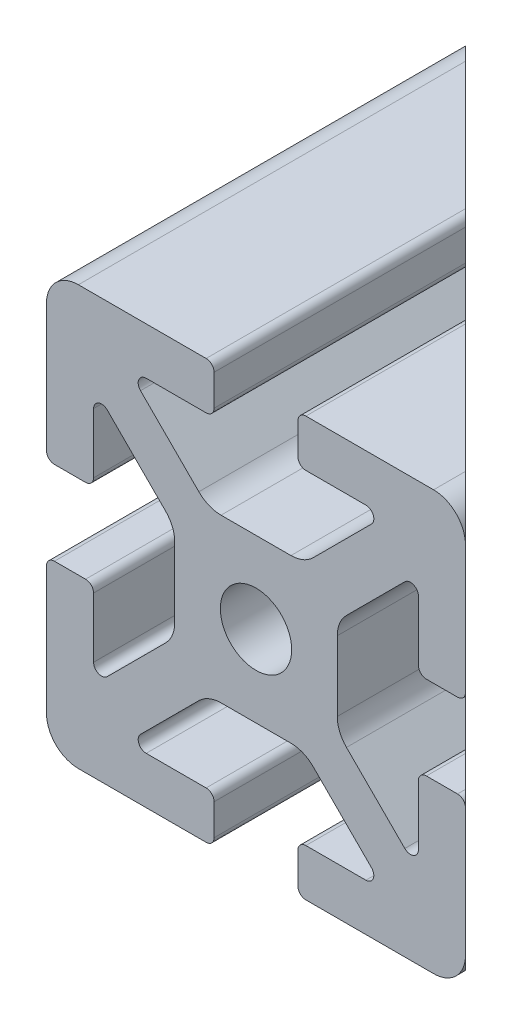
SolidWorks part; units mm, degrees
ref_plane "Front Plane" through (0, 0, 0) normal (0, 0, 1) x (1, 0, 0)
ref_plane "Top Plane" through (0, 0, 0) normal (0, 1, 0) x (1, 0, 0)
ref_plane "Right Plane" through (0, 0, 0) normal (1, 0, 0) x (0, 0, -1)
sketch "Sketch1" plane through (0, 0, 0) normal (0, 0, 1) x (1, 0, 0)
  line L0 (0, 20) -> (0, -20) construction
  line L1 (-20, 0) -> (20, 0) construction
  line L2 (-20, 16.952) -> (-20, 4.7625)
  line L3 (-16.952, 20) -> (-4.7625, 20)
  line L4 (-4.0005, 19.238) -> (-4.0005, 16.2662)
  line L5 (-4.7625, 15.5042) -> (-10.4856, 15.5042)
  line L6 (-11.0244, 14.2034) -> (-5.456, 8.6351)
  line L7 (-14.2034, 11.0244) -> (-8.6351, 5.456)
  line L8 (-15.5042, 10.4856) -> (-15.5042, 4.7625)
  line L9 (-16.2662, 4.0005) -> (-19.238, 4.0005)
  line L10 (0, 0) -> (-20, 20) construction
  line L11 (-3.3367, 7.7572) -> (3.3367, 7.7572)
  line L12 (-7.7572, 3.3367) -> (-7.7572, -3.3367)
  line L13 (16.2662, 4.0005) -> (19.238, 4.0005)
  line L14 (15.5042, 10.4856) -> (15.5042, 4.7625)
  line L15 (20, 16.952) -> (20, 4.7625)
  line L16 (16.952, 20) -> (4.7625, 20)
  line L17 (4.0005, 19.238) -> (4.0005, 16.2662)
  line L18 (4.7625, 15.5042) -> (10.4856, 15.5042)
  line L19 (7.7572, 3.3367) -> (7.7572, -3.3367)
  line L20 (11.0244, 14.2034) -> (5.456, 8.6351)
  line L21 (14.2034, 11.0244) -> (8.6351, 5.456)
  line L22 (-16.2662, -4.0005) -> (-19.238, -4.0005)
  line L23 (-15.5042, -10.4856) -> (-15.5042, -4.7625)
  line L24 (-14.2034, -11.0244) -> (-8.6351, -5.456)
  line L25 (-11.0244, -14.2034) -> (-5.456, -8.6351)
  line L26 (-4.7625, -15.5042) -> (-10.4856, -15.5042)
  line L27 (-4.0005, -19.238) -> (-4.0005, -16.2662)
  line L28 (-16.952, -20) -> (-4.7625, -20)
  line L29 (-20, -16.952) -> (-20, -4.7625)
  line L30 (20, -16.952) -> (20, -4.7625)
  line L31 (16.952, -20) -> (4.7625, -20)
  line L32 (4.0005, -19.238) -> (4.0005, -16.2662)
  line L33 (4.7625, -15.5042) -> (10.4856, -15.5042)
  line L34 (11.0244, -14.2034) -> (5.456, -8.6351)
  line L35 (14.2034, -11.0244) -> (8.6351, -5.456)
  line L36 (15.5042, -10.4856) -> (15.5042, -4.7625)
  line L37 (16.2662, -4.0005) -> (19.238, -4.0005)
  line L38 (-3.3367, -7.7572) -> (3.3367, -7.7572)
  circle A0 centre (0, 0) radius 3.4036
  arc A1 (-20, 16.952) -> (-16.952, 20) centre (-16.952, 16.952) cw
  arc A2 (-14.2034, 11.0244) -> (-15.5042, 10.4856) centre (-14.7422, 10.4856) ccw
  arc A3 (-10.4856, 15.5042) -> (-11.0244, 14.2034) centre (-10.4856, 14.7422) ccw
  arc A4 (-4.7625, 20) -> (-4.0005, 19.238) centre (-4.7625, 19.238) cw
  arc A5 (-20, 4.7625) -> (-19.238, 4.0005) centre (-19.238, 4.7625) ccw
  arc A6 (-15.5042, 4.7625) -> (-16.2662, 4.0005) centre (-16.2662, 4.7625) cw
  arc A7 (-4.0005, 16.2662) -> (-4.7625, 15.5042) centre (-4.7625, 16.2662) cw
  arc A8 (-3.3367, 7.7572) -> (-5.456, 8.6351) centre (-3.3367, 10.7544) cw
  arc A9 (-7.7572, 3.3367) -> (-8.6351, 5.456) centre (-10.7544, 3.3367) ccw
  arc A10 (15.5042, 4.7625) -> (16.2662, 4.0005) centre (16.2662, 4.7625) ccw
  arc A11 (20, 4.7625) -> (19.238, 4.0005) centre (19.238, 4.7625) cw
  arc A12 (20, 16.952) -> (16.952, 20) centre (16.952, 16.952) ccw
  arc A13 (4.7625, 20) -> (4.0005, 19.238) centre (4.7625, 19.238) ccw
  arc A14 (4.0005, 16.2662) -> (4.7625, 15.5042) centre (4.7625, 16.2662) ccw
  arc A15 (3.3367, 7.7572) -> (5.456, 8.6351) centre (3.3367, 10.7544) ccw
  arc A16 (7.7572, 3.3367) -> (8.6351, 5.456) centre (10.7544, 3.3367) cw
  arc A17 (14.2034, 11.0244) -> (15.5042, 10.4856) centre (14.7422, 10.4856) cw
  arc A18 (10.4856, 15.5042) -> (11.0244, 14.2034) centre (10.4856, 14.7422) cw
  arc A19 (-7.7572, -3.3367) -> (-8.6351, -5.456) centre (-10.7544, -3.3367) cw
  arc A20 (-3.3367, -7.7572) -> (-5.456, -8.6351) centre (-3.3367, -10.7544) ccw
  arc A21 (-4.0005, -16.2662) -> (-4.7625, -15.5042) centre (-4.7625, -16.2662) ccw
  arc A22 (-15.5042, -4.7625) -> (-16.2662, -4.0005) centre (-16.2662, -4.7625) ccw
  arc A23 (-20, -4.7625) -> (-19.238, -4.0005) centre (-19.238, -4.7625) cw
  arc A24 (-4.7625, -20) -> (-4.0005, -19.238) centre (-4.7625, -19.238) ccw
  arc A25 (-10.4856, -15.5042) -> (-11.0244, -14.2034) centre (-10.4856, -14.7422) cw
  arc A26 (-14.2034, -11.0244) -> (-15.5042, -10.4856) centre (-14.7422, -10.4856) cw
  arc A27 (-20, -16.952) -> (-16.952, -20) centre (-16.952, -16.952) ccw
  arc A28 (20, -16.952) -> (16.952, -20) centre (16.952, -16.952) cw
  arc A29 (14.2034, -11.0244) -> (15.5042, -10.4856) centre (14.7422, -10.4856) ccw
  arc A30 (10.4856, -15.5042) -> (11.0244, -14.2034) centre (10.4856, -14.7422) ccw
  arc A31 (4.7625, -20) -> (4.0005, -19.238) centre (4.7625, -19.238) cw
  arc A32 (20, -4.7625) -> (19.238, -4.0005) centre (19.238, -4.7625) ccw
  arc A33 (15.5042, -4.7625) -> (16.2662, -4.0005) centre (16.2662, -4.7625) cw
  arc A34 (4.0005, -16.2662) -> (4.7625, -15.5042) centre (4.7625, -16.2662) cw
  arc A35 (3.3367, -7.7572) -> (5.456, -8.6351) centre (3.3367, -10.7544) cw
  arc A36 (7.7572, -3.3367) -> (8.6351, -5.456) centre (10.7544, -3.3367) ccw
  point P29 (-20, 4.0005)
  point P32 (-15.5042, 4.0005)
  point P36 (-4.5782, 7.7572)
  point P68 (0, 7.7572)
  dimension "D4" = 6.8072
  dimension "D5" = 3.048
  dimension "D6" = 0.762
  dimension "D9" = 0.762
  dimension "D10" = 0.762
  dimension "D11" = 4.4958
  dimension "D13" = 2.9972
  dimension "D1" = 40
  dimension "D2" = 40
  dimension "D3" = 12.2428
  dimension "D7" = 8.001
  dimension "D8" = 4.4958
extrude "Extrude1" add sketch "Sketch1" along normal mid plane 40
ref_plane "Plane1" through (16.952, -20, -20) normal (1, 0, 0) x (0, 0, -1)
sketch "Sketch3" plane through (0, -20, 0) normal (0, -1, 0) x (1, 0, 0)
  line L0 (20, 20) -> (-20, -20)
  line L1 (-20, -20) -> (20, -20)
  line L2 (20, -20) -> (20, 20)
  point P0 (20, 20)
  point P1 (-20, -20)
extrude "Cut-Extrude1" cut sketch "Sketch3" against normal through all
equation "\"D2@Sketch1\" = \"D1@Sketch1\""
